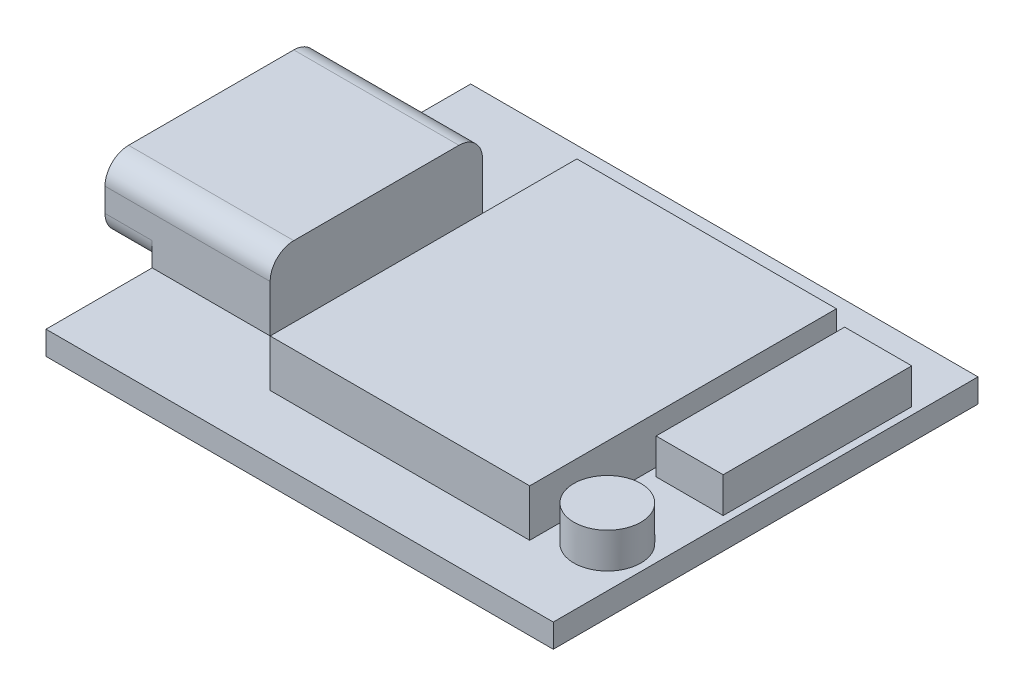
SolidWorks part; units mm, degrees
ref_plane "Front Plane" through (0, 0, 0) normal (0, 0, 1) x (1, 0, 0)
ref_plane "Top Plane" through (0, 0, 0) normal (0, 1, 0) x (1, 0, 0)
ref_plane "Right Plane" through (0, 0, 0) normal (1, 0, 0) x (0, 0, -1)
sketch "Sketch1" plane through (0, 0, 0) normal (0, 1, 0) x (1, 0, 0)
  line L1 (10.75, 9) -> (-10.75, 9)
  line L2 (10.75, 9) -> (10.75, -9)
  line L3 (10.75, -9) -> (-10.75, -9)
  line L4 (-10.75, 9) -> (-10.75, -9)
  line L5 (10.75, 9) -> (-10.75, -9) construction
  line L6 (10.75, -9) -> (-10.75, 9) construction
  point P0 (0, 0)
  dimension "D1" = 21.5
  dimension "D2" = 18
extrude "Boss-Extrude1" add sketch "Sketch1" along normal blind 1
sketch "Sketch2" plane through (0, 1, 0) normal (0, 1, 0) x (1, 0, 0)
  line L0 (-10.75, 9) -> (-10.75, -9) construction
  line L1 (-12.75, 4.5) -> (-5.75, 4.5)
  line L2 (-12.75, 4.5) -> (-12.75, -4.5)
  line L3 (-12.75, -4.5) -> (-5.75, -4.5)
  line L4 (-5.75, 4.5) -> (-5.75, -4.5)
  point P4 (-5.75, 0)
  dimension "D1" = 7
  dimension "D2" = 9
  dimension "D3" = 2
extrude "Boss-Extrude2" add sketch "Sketch2" along normal blind 3
fillet "Fillet1" radius 1 4 edges at (-11.75, 1, -4.5) (-11.75, 1, 4.5) (-9.25, 4, -4.5) (-9.25, 4, 4.5)
sketch "Sketch3" plane through (0, 1, 0) normal (0, 1, 0) x (1, 0, 0)
  line L0 (10.75, -9) -> (10.75, 9) construction
  line L1 (7.25, -6.5) -> (-3.75, -6.5)
  line L2 (7.25, -6.5) -> (7.25, 6.5)
  line L3 (7.25, 6.5) -> (-3.75, 6.5)
  line L4 (-3.75, -6.5) -> (-3.75, 6.5)
  line L5 (7.25, -6.5) -> (-3.75, 6.5) construction
  line L6 (7.25, 6.5) -> (-3.75, -6.5) construction
  point P0 (1.75, 0)
  point P5 (0, 0)
  dimension "D1" = 11
  dimension "D2" = 13
  dimension "D3" = 9
extrude "Boss-Extrude3" add sketch "Sketch3" along normal blind 2
sketch "Sketch4" plane through (0, 1, 0) normal (0, 1, 0) x (1, 0, 0)
  line L1 (7.5991, 6.5) -> (10.4421, 6.5)
  line L2 (7.5991, 6.5) -> (7.5991, -1.4917)
  line L3 (7.5991, -1.4917) -> (10.4421, -1.4917)
  line L4 (10.4421, 6.5) -> (10.4421, -1.4917)
  circle A0 centre (9.0206, -4.9784) radius 1.4215
extrude "Boss-Extrude5" add sketch "Sketch4" along normal blind 1.5
